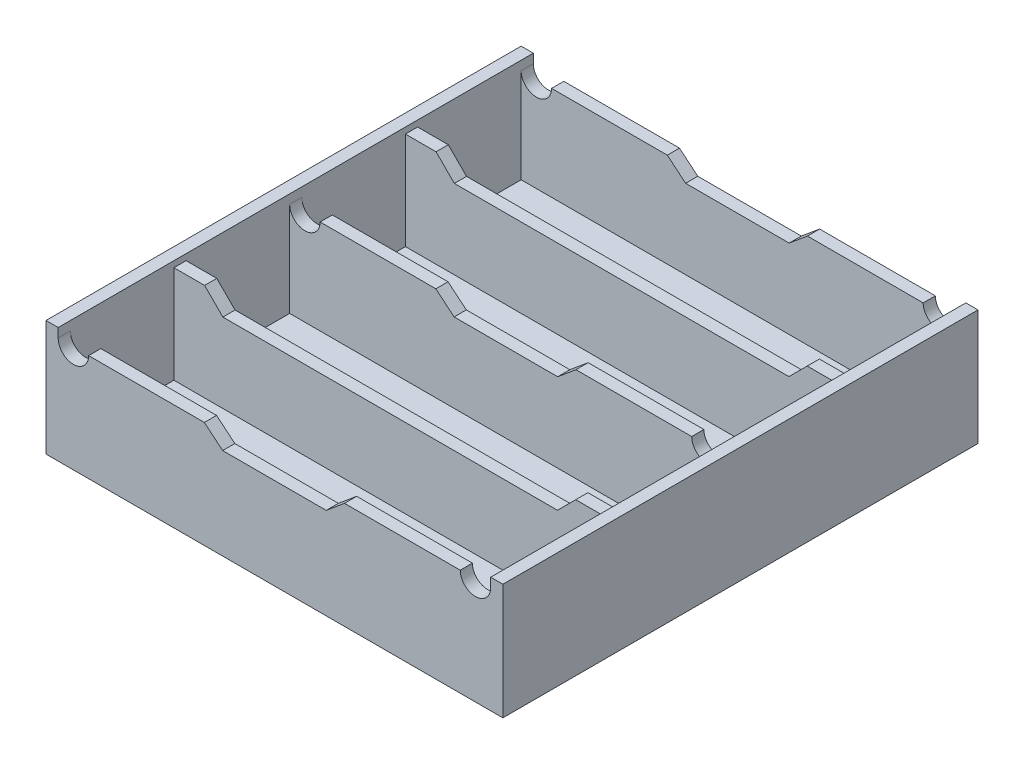
SolidWorks part; units mm, degrees
ref_plane "Front Plane" through (0, 0, 0) normal (0, 0, 1) x (1, 0, 0)
ref_plane "Top Plane" through (0, 0, 0) normal (0, 1, 0) x (1, 0, 0)
ref_plane "Right Plane" through (0, 0, 0) normal (1, 0, 0) x (0, 0, -1)
sketch "Sketch1" plane through (0, 0, 0) normal (0, 1, 0) x (1, 0, 0)
  line L1 (0, 0) -> (75, 0)
  line L2 (0, 0) -> (0, 40)
  line L3 (0, 40) -> (75, 40)
  line L4 (75, 0) -> (75, 40)
  dimension "D1" = 75
  dimension "D2" = 40
extrude "Boss-Extrude1" add sketch "Sketch1" along normal blind 2
sketch "Sketch2" plane through (0, 2, 0) normal (0, 1, 0) x (1, 0, 0)
  line L1 (2, 38) -> (73, 38)
  line L2 (2, 38) -> (2, 21)
  line L3 (2, 21) -> (73, 21)
  line L4 (73, 38) -> (73, 21)
  line L5 (2, 19) -> (73, 19)
  line L6 (2, 19) -> (2, 2)
  line L7 (2, 2) -> (73, 2)
  line L8 (73, 19) -> (73, 2)
  line L9 (0, 40) -> (75, 40)
  line L10 (0, 40) -> (0, 0)
  line L11 (0, 0) -> (75, 0)
  line L12 (75, 40) -> (75, 0)
  point P14 (0, 20)
  dimension "D1" = 2
  dimension "D2" = 2
  dimension "D3" = 2
  dimension "D4" = 2
  dimension "D5" = 2
  dimension "D6" = 1
extrude "Boss-Extrude2" add sketch "Sketch2" along normal blind 17
sketch "Sketch3" plane through (0, 0, 0) normal (0, 0, 1) x (1, 0, 0)
  line L0 (2, 17.5) -> (2, 19)
  line L1 (2, 19) -> (2, 2) construction
  line L2 (2, 19) -> (73, 19)
  line L3 (73, 19) -> (73, 17.5)
  line L4 (73, 19) -> (73, 2) construction
  line L5 (7, 17.5) -> (26, 17.5)
  line L6 (26, 17.5) -> (29, 15)
  line L7 (29, 15) -> (46, 15)
  line L8 (46, 15) -> (49, 17.5)
  line L9 (49, 17.5) -> (68, 17.5)
  arc A0 (2, 17.5) -> (7, 17.5) centre (4.5, 17.5) ccw
  arc A1 (68, 17.5) -> (73, 17.5) centre (70.5, 17.5) ccw
  point P11 (37.5, 15)
  point P21 (37.5, 19)
  dimension "D1" = 5
  dimension "D2" = 17
  dimension "D3" = 3
  dimension "D4" = 1.5
extrude "Cut-Extrude2" cut sketch "Sketch3" against normal blind 17 contours L6 L7 L8 L9 A1 L3 L2 L0 A0 L5
ref_plane "Plane1" through (0, 0, -20) normal (0, 0, 1) x (1, 0, 0)
mirror "Mirror1" about plane through (0, 0, -20) normal (0, 0, 1) of "Cut-Extrude2"
sketch "Sketch4" plane through (0, 0, -19) normal (0, 0, 1) x (1, 0, 0)
  line L0 (2, 18) -> (7.0359, 18)
  line L1 (2, 19) -> (2, 2) construction
  line L2 (7.0359, 18) -> (10.0359, 15)
  line L3 (10.0359, 15) -> (64.9641, 15)
  line L4 (64.9641, 15) -> (67.9641, 18)
  line L5 (67.9641, 18) -> (73, 18)
  line L6 (73, 19) -> (73, 2) construction
  line L7 (46, 15) -> (29, 15) construction
  line L9 (73, 19) -> (2, 19) construction
  line L10 (2, 18) -> (2, 19)
  line L11 (2, 19) -> (73, 19)
  line L12 (73, 19) -> (73, 18)
  dimension "D1" = 1
  dimension "D2" = 3
extrude "Cut-Extrude3" cut sketch "Sketch4" against normal up to next contours L2 L3 L4 L5 L12 L11 L10 L0
sketch "Sketch5" plane through (0, 2, 0) normal (0, 1, 0) x (1, 0, 0)
  line L0 (2, 38) -> (2, 21) construction
  line L1 (2, 19) -> (2, 2) construction
  line L2 (73, 38) -> (2, 38) construction
  circle A0 centre (37.5, 29.5) radius 1.6
  circle A1 centre (37.5, 10.5) radius 1.6
  point P4 (2, 29.5)
  point P5 (2, 10.5)
  point P8 (37.5, 38)
  dimension "D1" = 3.2
extrude "Cut-Extrude4" cut sketch "Sketch5" against normal up to next
ref_plane "Plane2" through (0, 0, -1) normal (0, 0, 1) x (1, 0, 0)
mirror "Mirror2" about plane through (0, 0, -1) normal (0, 0, 1) of "Cut-Extrude4", "Cut-Extrude3", "Mirror1", "Cut-Extrude2", "Boss-Extrude2", "Boss-Extrude1"
